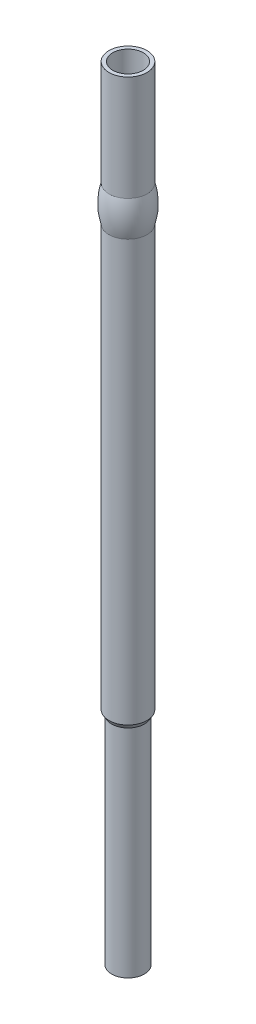
SolidWorks part; units mm, degrees
material "Nickel silver 65-12, UNS C75700"
ref_plane "Front" through (0, 0, 0) normal (0, 0, 1) x (1, 0, 0)
ref_plane "Top" through (0, 0, 0) normal (0, 1, 0) x (1, 0, 0)
ref_plane "Right" through (0, 0, 0) normal (1, 0, 0) x (0, 0, -1)
sketch "Sketch1" plane through (0, 0, 0) normal (1, 0, 0) x (0, 0, -1)
  line L0 (0.345, 0) -> (0.345, -12.56)
  line L1 (0.345, -12.56) -> (0, -12.56)
  line L2 (0, -12.56) -> (0, -12.8)
  line L3 (0, -12.8) -> (0.28, -12.8)
  line L4 (0.28, -12.8) -> (0.28, -17.7)
  line L5 (0.28, -17.7) -> (0.37, -17.7)
  line L6 (0.37, -17.7) -> (0.37, -12.8)
  line L7 (0.37, -12.8) -> (0.43, -12.7)
  line L8 (0.43, -12.7) -> (0.43, -3.18)
  line L9 (0.43, -3.18) -> (0.43, -2.38) construction
  line L10 (0.43, -2.38) -> (0.43, 0)
  line L11 (0.43, 0) -> (0.345, 0)
  arc A0 (0.43, -2.38) -> (0.43, -3.18) centre (-0.997, -2.78) cw
  point P11 (0.485, -2.78)
  dimension "D1" = 0.28
  dimension "D2" = 0.37
  dimension "D3" = 0.43
  dimension "D4" = 0.345
  dimension "D5" = 17.7
  dimension "D7" = 0.485
  dimension "D8" = 3.18
  dimension "D9" = 12.56
  dimension "D10" = 4.9
  dimension "D11" = 0.8
  dimension "D6" = 12.7
revolve "Revolve1" add sketch "Sketch1" angle 360 about L2
equation "\"D9@Sketch1\"=9.9-21.9+24.56"
equation "\"D1@Sketch1\"=0.56/2"
equation "\"D2@Sketch1\"=0.74/2"
equation "\"D7@Sketch1\"=0.97/2"
equation "\"D3@Sketch1\"=0.86/2"
equation "\"D4@Sketch1\"=0.69/2"
